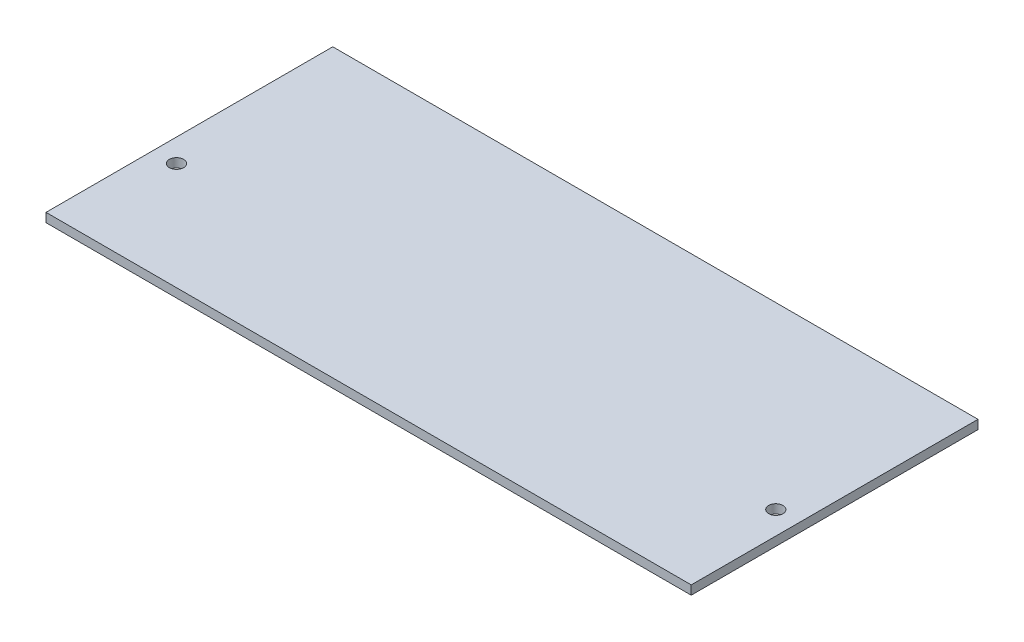
SolidWorks part; units mm, degrees
ref_plane "Front Plane" through (0, 0, 0) normal (0, 0, 1) x (1, 0, 0)
ref_plane "Top Plane" through (0, 0, 0) normal (0, 1, 0) x (1, 0, 0)
ref_plane "Right Plane" through (0, 0, 0) normal (1, 0, 0) x (0, 0, -1)
sketch "Sketch1" plane through (0, 0, 0) normal (0, 1, 0) x (1, 0, 0)
  line L1 (-39.2904, 44.3076) -> (189.3096, 44.3076)
  line L2 (-39.2904, 44.3076) -> (-39.2904, -57.2924)
  line L3 (-39.2904, -57.2924) -> (189.3096, -57.2924)
  line L4 (189.3096, 44.3076) -> (189.3096, -57.2924)
  dimension "D1" = 101.6
  dimension "D2" = 228.6
extrude "Boss-Extrude1" add sketch "Sketch1" along normal blind 3.175
sketch "Sketch2" plane through (0, 0, 0) normal (0, -1, 0) x (-1, 0, 0)
  line L0 (39.2904, 44.3076) -> (39.2904, -57.2924) construction
  line L1 (-189.3096, -57.2924) -> (-189.3096, 44.3076) construction
  circle A0 centre (31.1624, -19.1924) radius 2.54
  circle A1 centre (-181.1816, -19.1924) radius 2.54
  dimension "D1" = 5.08
  dimension "D3" = 5.08
  dimension "D2" = 8.128
  dimension "D4" = 8.128
extrude "Cut-Extrude1" cut sketch "Sketch2" against normal blind 3.175
